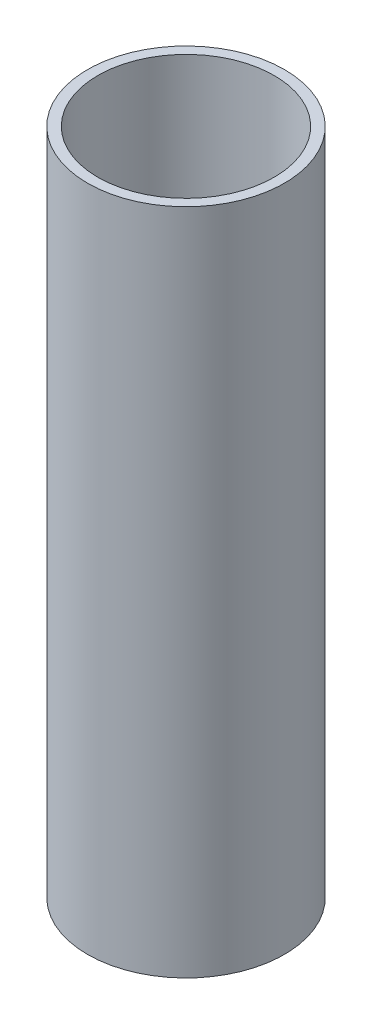
SolidWorks part; units mm, degrees
ref_plane "Front Plane" through (0, 0, 0) normal (0, 0, 1) x (1, 0, 0)
ref_plane "Top Plane" through (0, 0, 0) normal (0, 1, 0) x (1, 0, 0)
ref_plane "Right Plane" through (0, 0, 0) normal (1, 0, 0) x (0, 0, -1)
sketch "Sketch1" plane through (0, 0, 0) normal (0, 1, 0) x (1, 0, 0)
  line L0 (-9.5976, -16.9755) -> (7.4309, 40.2226) construction
  line L1 (-7.2538, -17.6732) -> (-11.9414, -16.2777) construction
  line L2 (9.9797, 15.7299) -> (12.2574, 11.4016) construction
  circle A0 centre (-4.1296, 1.3913) radius 19.1634
  circle A1 centre (-4.1296, 1.3913) radius 17.1634
  dimension "D1" = 2
extrude "Boss-Extrude1" add sketch "Sketch1" along normal mid plane 130
